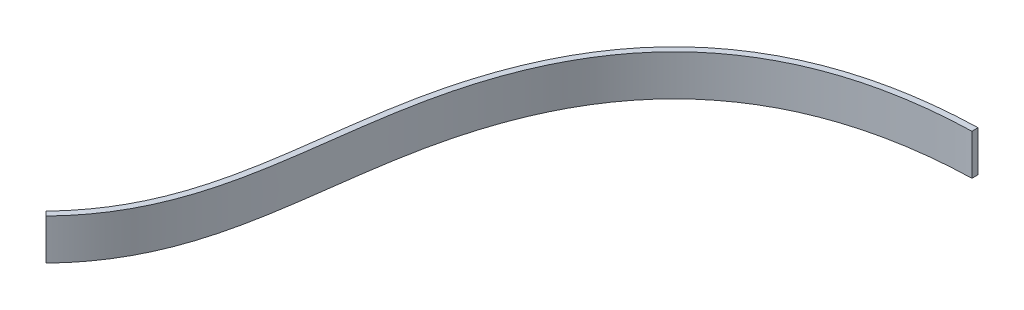
SolidWorks part; units mm, degrees
ref_plane "Front Plane" through (0, 0, 0) normal (0, 0, 1) x (1, 0, 0)
ref_plane "Top Plane" through (0, 0, 0) normal (0, 1, 0) x (1, 0, 0)
ref_plane "Right Plane" through (0, 0, 0) normal (1, 0, 0) x (0, 0, -1)
sketch "Sketch1" plane through (0, 0, 0) normal (0, 1, 0) x (1, 0, 0)
  line L0 (-456.4185, 38.6485) -> (143.5815, 38.6485) construction
  line L1 (-47.4219, 36.5556) -> (-49.5713, 38.6485)
  line L2 (143.6607, 299.6495) -> (143.5815, 302.6485)
  spline S0 degree 3 poles (143.5815, 302.6485) (42.6183, 299.9811) (-24.1529, 186.9501) (-11.2399, 78.0161) (-49.5713, 38.6485) knots 0 0 0 0 0.513499 1 1 1 1
  spline S1 degree 1 poles (143.6607, 299.6495) (-47.4219, 36.5556) knots 0 0 1 1 construction
  spline S2 degree 3 poles (143.6607, 299.6495) (142.157, 299.6098) (139.1285, 299.5036) (133.2501, 299.1931) (126.113, 298.6208) (117.9161, 297.6504) (107.4527, 295.9916) (95.2331, 293.2591) (81.8764, 289.0058) (69.7584, 283.857) (55.1591, 275.8995) (39.654, 264.0898) (24.8892, 247.4958) (13.4602, 229.0248) (4.8971, 209.2477) (-1.2702, 188.7493) (-5.4838, 168.1746) (-8.4806, 147.726) (-11.0689, 127.5411) (-14.0544, 107.777) (-17.5624, 91.7843) (-21.4029, 79.3606) (-24.9069, 70.2526) (-29.1402, 61.3812) (-33.3626, 54.2103) (-37.206, 48.6239) (-40.3367, 44.51) (-43.7138, 40.49) (-46.1716, 37.8397) (-47.4219, 36.5556) knots 0 0 0 0 0.007812 0.015625 0.03125 0.046875 0.0625 0.09375 0.125 0.15625 0.1875 0.25 0.3125 0.375 0.4375 0.5 0.5625 0.625 0.6875 0.75 0.8125 0.84375 0.875 0.90625 0.9375 0.953125 0.96875 0.984375 1 1 1 1
  dimension "D1" = 3
extrude "Boss-Extrude1" add sketch "Sketch1" along normal blind 20
